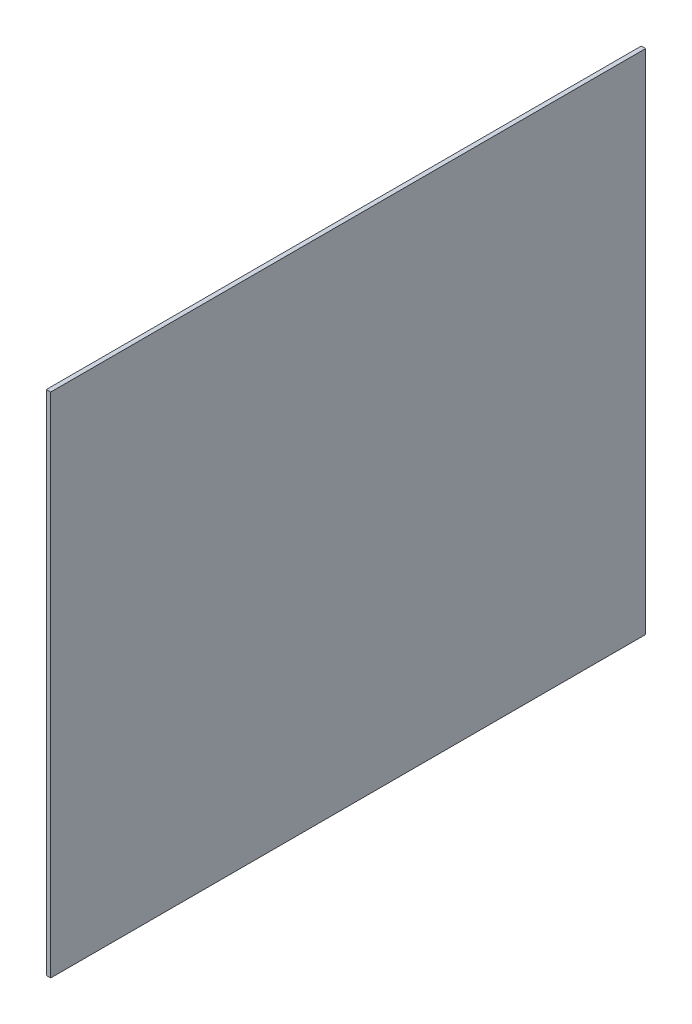
SolidWorks part; units mm, degrees
material "ABS PC"
ref_plane "Front Plane" through (0, 0, 0) normal (0, 0, 1) x (1, 0, 0)
ref_plane "Top Plane" through (0, 0, 0) normal (0, 1, 0) x (1, 0, 0)
ref_plane "Right Plane" through (0, 0, 0) normal (1, 0, 0) x (0, 0, -1)
sketch "Sketch1" plane through (0, 0, 0) normal (0, 0, 1) x (1, 0, 0)
  line L5 (-1.5875, 184.15) -> (1.5875, 184.15)
  line L6 (-1.5875, 184.15) -> (-1.5875, -184.15)
  line L7 (-1.5875, -184.15) -> (1.5875, -184.15)
  line L8 (1.5875, 184.15) -> (1.5875, -184.15)
  line L9 (-1.5875, 184.15) -> (1.5875, -184.15) construction
  line L10 (-1.5875, -184.15) -> (1.5875, 184.15) construction
  point P0 (0, 0)
  point P1 (0, 0)
  dimension "D1" = 368.3
  dimension "D2" = 3.175
extrude "Boss-Extrude1" add sketch "Sketch1" along normal blind 431.8
